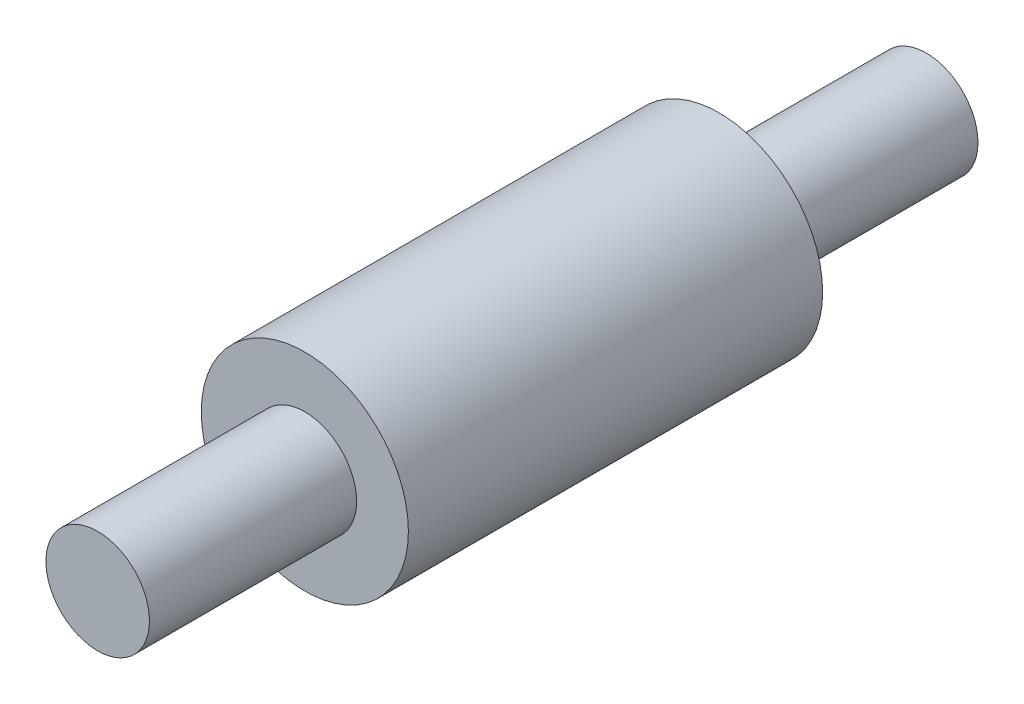
SolidWorks part; units mm, degrees
ref_plane "Ön Düzlem" through (0, 0, 0) normal (0, 0, 1) x (1, 0, 0)
ref_plane "Üst Düzlem" through (0, 0, 0) normal (0, 1, 0) x (1, 0, 0)
ref_plane "Sağ Düzlem" through (0, 0, 0) normal (1, 0, 0) x (0, 0, -1)
sketch "Sketch1" plane through (0, 0, 0) normal (0, 0, 1) x (1, 0, 0)
  circle A0 centre (0, 0) radius 2.5
  dimension "D1" = 5
extrude "Boss-Extrude1" add sketch "Sketch1" along normal blind 10
sketch "Sketch2" plane through (0, 0, 10) normal (0, 0, 1) x (1, 0, 0)
  circle A0 centre (0, 0) radius 5
  dimension "D1" = 10
extrude "Boss-Extrude2" add sketch "Sketch2" along normal blind 20
sketch "Sketch3" plane through (0, 0, 30) normal (0, 0, 1) x (1, 0, 0)
  circle A0 centre (0, 0) radius 2.5
  dimension "D1" = 5
extrude "Boss-Extrude3" add sketch "Sketch3" along normal blind 10
